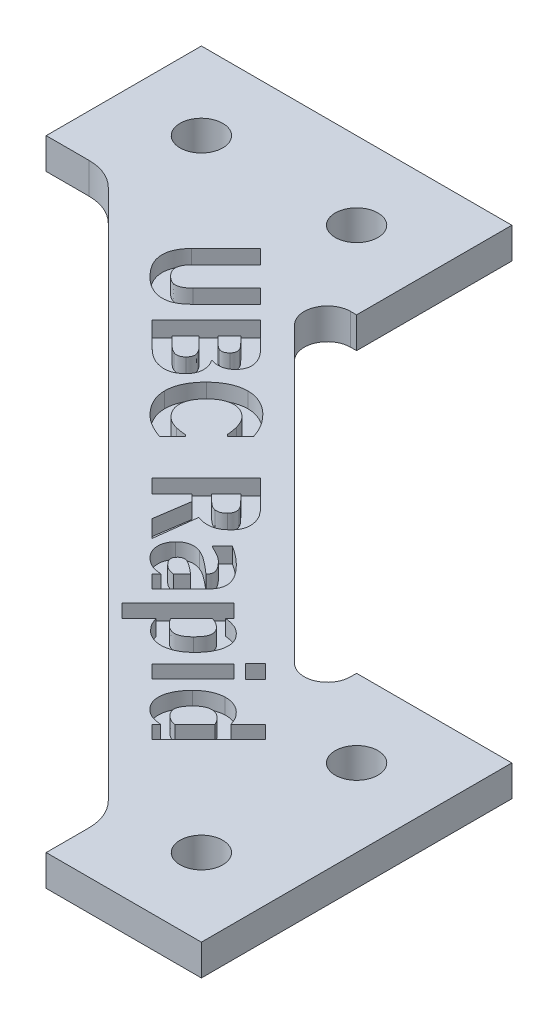
SolidWorks part; units mm, degrees
ref_plane "Front Plane" through (0, 0, 0) normal (0, 0, 1) x (1, 0, 0)
ref_plane "Top Plane" through (0, 0, 0) normal (0, 1, 0) x (1, 0, 0)
ref_plane "Right Plane" through (0, 0, 0) normal (1, 0, 0) x (0, 0, -1)
sketch "Sketch1" plane through (0, 0, 0) normal (0, 1, 0) x (1, 0, 0)
  line L0 (8, -20) -> (80, -92)
  line L1 (0, 0) -> (40, 0)
  line L2 (0, 0) -> (0, -20)
  line L3 (0, -20) -> (40, -20)
  line L4 (40, 0) -> (40, -20)
  line L5 (80, -60) -> (100, -60)
  line L6 (80, -60) -> (80, -100)
  line L7 (80, -100) -> (100, -100)
  line L8 (100, -60) -> (100, -100)
  line L9 (32, -20) -> (80, -68)
  arc A0 (5.5147, -20) -> (9.7574, -21.7574) centre (5.5147, -26) cw
  arc A1 (39.2426, -20) -> (37.1213, -25.1213) centre (39.2426, -23) ccw
  arc A2 (74.8787, -62.8787) -> (80, -60.7574) centre (77, -60.7574) ccw
  arc A3 (78.2426, -90.2426) -> (80, -94.4853) centre (74, -94.4853) cw
  dimension "D10" = 6
  dimension "D11" = 3
  dimension "D12" = 6
  dimension "D13" = 3
  dimension "D1" = 40
  dimension "D2" = 20
  dimension "D3" = 40
  dimension "D4" = 20
  dimension "D5" = 80
  dimension "D6" = 80
  dimension "D7" = 45
  dimension "D8" = 24
  dimension "D9" = 8
extrude "Boss-Extrude1" add sketch "Sketch1" along normal blind 4 contours L8 L5 L6 L7 | A2 L9 L6 | A1 L3 L9 | L4 L1 L2 L3 | L9 L3 L0 L6 | L0 A3 L6 | L3 A0 L0
sketch "Sketch2" plane through (0, 4, 0) normal (0, 1, 0) x (1, 0, 0)
  line L0 (0, -10) -> (40, -10) construction
  line L1 (0, 0) -> (0, -20) construction
  line L2 (40, 0) -> (40, -20) construction
  line L3 (20, 0) -> (20, -46.815) construction
  line L4 (0, 0) -> (40, 0) construction
  line L5 (90, -100) -> (90, -60) construction
  line L6 (80, -100) -> (100, -100) construction
  line L7 (80, -60) -> (100, -60) construction
  line L8 (100, -80) -> (48.3842, -80) construction
  line L9 (100, -60) -> (100, -100) construction
  circle A0 centre (10, -10) radius 2.75
  circle A1 centre (30, -10) radius 2.75
  circle A2 centre (90, -70) radius 2.75
  circle A3 centre (90, -90) radius 2.75
  dimension "D1" = 5.5
  dimension "D2" = 10
  dimension "D3" = 10
extrude "Cut-Extrude1" cut sketch "Sketch2" against normal through all
sketch "Sketch3" plane through (0, 4, 0) normal (0, 1, 0) x (1, 0, 0)
  line L0 (13.6569, -20) -> (80, -86.3431) construction
  line L1 (9.7574, -21.7574) -> (78.2426, -90.2426) construction
  line L2 (0, -20) -> (5.5147, -20) construction
  line L3 (80, -94.4853) -> (80, -100) construction
  text T0 "UBC Rapid" font "Verdana" height 10
  dimension "D1" = 4
extrude "Cut-Extrude2" cut sketch "Sketch3" against normal blind 2
